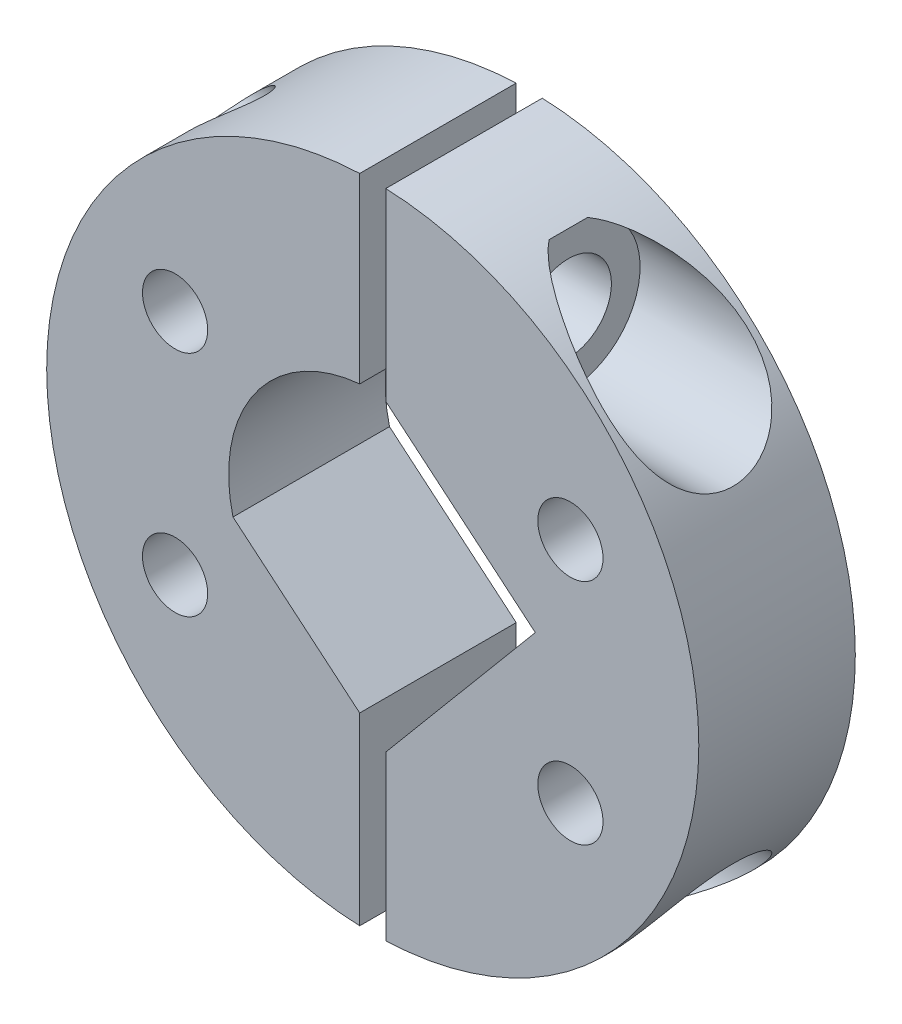
SolidWorks part; units mm, degrees
material "ABS"
ref_plane "정면" through (0, 0, 0) normal (0, 0, 1) x (1, 0, 0)
ref_plane "윗면" through (0, 0, 0) normal (0, 1, 0) x (1, 0, 0)
ref_plane "우측면" through (0, 0, 0) normal (1, 0, 0) x (0, 0, -1)
sketch "스케치7" plane through (0, 0, 0) normal (0, 0, 1) x (1, 0, 0)
  line L0 (12.4643, 1.2246) -> (0.9584, -12.4876)
  line L1 (12.4643, 1.2246) -> (0.7898, 11.0207)
  line L2 (0.9584, -12.4876) -> (-10.7161, -2.6915)
  line L3 (0.7898, 11.0207) -> (-10.7161, -2.6915) construction
  line L5 (0, 0) -> (-8.464, 7.1021) construction
  line L6 (0, 11.0489) -> (0, 25) construction
  arc A0 (-10.7161, -2.6915) -> (0.7898, 11.0207) centre (0, 0) cw
  circle A1 centre (0, 0) radius 25
  circle A2 centre (0, 0) radius 11.0489 construction
  dimension "D3" = 15.24
  dimension "D5" = 50
  dimension "D2" = 17.9
  dimension "D4" = 50
  dimension "D1" = 19.81
extrude "보스-돌출1" add sketch "스케치7" along normal mid plane 12 contours A1 | L0 L2 A0 L1
sketch "스케치19" plane through (0, 0, 0) normal (0, 0, 1) x (1, 0, 0)
  line L0 (0, 25) -> (0, -25) construction
  line L1 (1, 24.98) -> (1, -24.98)
  line L2 (-1, 24.98) -> (-1, -24.98)
  circle A0 centre (0, 0) radius 25 construction
  arc A1 (-1, -24.98) -> (1, -24.98) centre (0, 0) ccw
  arc A2 (1, 24.98) -> (-1, 24.98) centre (0, 0) ccw
  dimension "D1" = 2
extrude "컷-돌출1" cut sketch "스케치19" against normal through all both and the other way through all
hole_wizard "M6x1.0 나사 구멍1" positions "스케치17" profile "스케치18" tap size "M6x1.0" standard "Ansi Metric"
sketch "스케치17" plane through (0, 0, 6) normal (0, 0, 1) x (1, 0, 0)
  line L0 (0, 0) -> (17.5, 0) construction
  line L3 (0, 0) -> (15.1554, 8.75) construction
  circle A0 centre (0, 0) radius 17.5 construction
  arc A3 (-1, 11.0036) -> (-10.7161, -2.6915) centre (0, 0) ccw construction
  point P19 (0, -17.5)
  point P22 (0, 17.5)
  point P32 (15.1554, -8.75)
  point P34 (15.1554, 8.75)
  dimension "D2" = 30
  dimension "D1" = 35
sketch "스케치18" plane through (15.1554, 8.75, 6) normal (1, 0, 0) x (0, -1, 0)
  line L0 (0, 0) -> (0, 12)
  line L1 (0, 12) -> (2.5, 12)
  line L2 (2.5, 12) -> (2.5, 0)
  line L5 (2.5, 0) -> (0, 0)
  line L11 (0, -6.35) -> (0, 107.95) construction
  dimension "관통 탭 드릴 지름" = 5
  dimension "관통 탭 드릴 깊이" = 12
cosmetic thread "구멍 나사산10" parameters "D1"=12, "D2"=6
pattern_circular "원형 패턴2" count 6 over 360 about axis through (0, 0, 0) along (0, 0, 1) skipping 2, 5 of "M6x1.0 나사 구멍1"
ref_plane "평면1" through (15, 0, 0) normal (1, 0, 0) x (0, 0, -1)
hole_wizard "M6 소켓 머리 캡 나사용 카운터보어1" positions "스케치22" profile "스케치23" counterbore size "M6" standard "Ansi Metric" end condition through all
sketch "스케치22" plane through (15, 0, 0) normal (1, 0, 0) x (0, 0, -1)
  line L0 (-6, 0) -> (6, 0) construction
  line L1 (-6, 24.98) -> (-6, -24.98) construction
  line L2 (6, -24.98) -> (6, 24.98) construction
  line L4 (0, 25) -> (0, 11.0489) construction
  point P0 (0, 18.0245)
  point P2 (0, -18.0245)
sketch "스케치23" plane through (15, 18.0245, 0) normal (0, 1, 0) x (0, 0, -1)
  line L0 (0, 0) -> (0, 40)
  line L1 (0, 40) -> (3.3, 40)
  line L3 (3.3, 40) -> (3.3, 6)
  line L4 (3.3, 6) -> (5.5, 6)
  line L5 (5.5, 6) -> (5.5, 0)
  line L7 (5.5, 0) -> (0, 0)
  line L11 (0, -6.35) -> (0, 107.95) construction
  dimension "관통 구멍 지름" = 6.6
  dimension "관통 구멍 깊이" = 40
  dimension "카운터보어 지름" = 11
  dimension "카운터보어 깊이" = 6
hole_wizard "M6x1.0 나사 구멍3" positions "스케치28" profile "스케치29" tap size "M6x1.0" standard "Ansi Metric" end condition through all
sketch "스케치28" plane through (15, 0, 0) normal (1, 0, 0) x (0, 0, -1)
  point P0 (0, 18.0245)
  point P3 (0, -18.0245)
sketch "스케치29" plane through (15, 18.0245, 0) normal (0, 1, 0) x (0, 0, -1)
  line L0 (0, 0) -> (0, 40)
  line L1 (0, 40) -> (2.5, 40)
  line L2 (2.5, 40) -> (2.5, 0)
  line L5 (2.5, 0) -> (0, 0)
  line L11 (0, -6.35) -> (0, 107.95) construction
  dimension "관통 탭 드릴 지름" = 5
  dimension "관통 탭 드릴 깊이" = 40
cosmetic thread "구멍 나사산8" parameters "D2"=6
cosmetic thread "구멍 나사산9" parameters "D2"=6
sketch "스케치30" plane through (15, 0, 0) normal (1, 0, 0) x (0, 0, -1)
  circle A0 centre (0, 18.0245) radius 5.5
  arc A1 (-5.133, 20) -> (5.133, 20) centre (0, 18.0245) ccw construction
  circle A2 centre (0, -18.0245) radius 5.5
  arc A4 (5.133, -20) -> (-5.133, -20) centre (0, -18.0245) ccw construction
extrude "컷-돌출2" cut sketch "스케치30" along normal through all
